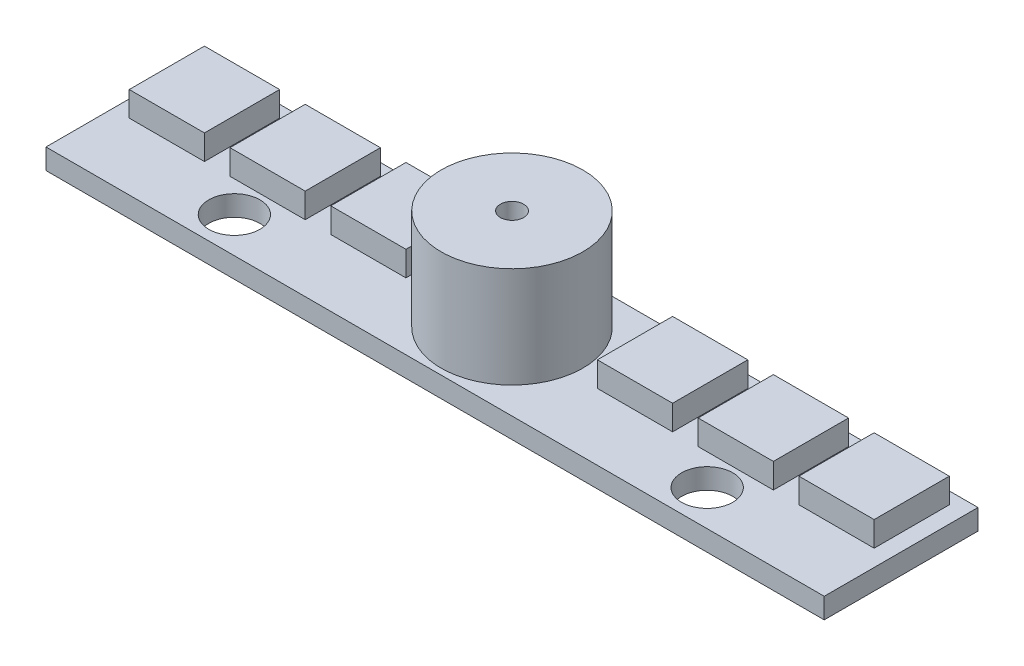
SolidWorks part; units mm, degrees
ref_plane "Front Plane" through (0, 0, 0) normal (0, 0, 1) x (1, 0, 0)
ref_plane "Top Plane" through (0, 0, 0) normal (0, 1, 0) x (1, 0, 0)
ref_plane "Right Plane" through (0, 0, 0) normal (1, 0, 0) x (0, 0, -1)
sketch "Sketch1" plane through (0, 0, 0) normal (0, 1, 0) x (1, 0, 0)
  line L0 (0, 4.96) -> (0, -4.96) construction
  line L1 (-25.1, 4.96) -> (25.1, 4.96)
  line L2 (-25.1, 4.96) -> (-25.1, -4.96)
  line L3 (-25.1, -4.96) -> (25.1, -4.96)
  line L4 (25.1, 4.96) -> (25.1, -4.96)
  line L5 (-25.1, 4.96) -> (25.1, -4.96) construction
  line L6 (-25.1, -4.96) -> (25.1, 4.96) construction
  line L7 (-25.1, -2.66) -> (25.1, -2.66) construction
  circle A0 centre (-15.25, -2.66) radius 1.65
  circle A1 centre (15.25, -2.66) radius 1.65
  point P0 (0, 0)
  dimension "D4" = 3.3
  dimension "D1" = 9.92
  dimension "D2" = 50.2
  dimension "D3" = 2.3
  dimension "D5" = 30.5
extrude "Boss-Extrude1" add sketch "Sketch1" along normal blind 1.32
sketch "Sketch2" plane through (0, 1.32, 0) normal (0, 1, 0) x (1, 0, 0)
  line L0 (0, 4.96) -> (0, -4.96) construction
  line L1 (25.1, 4.96) -> (-25.1, 4.96) construction
  line L2 (-25.1, -4.96) -> (25.1, -4.96) construction
  circle A0 centre (0, 0) radius 4.575
  dimension "D1" = 9.15
extrude "Boss-Extrude2" add sketch "Sketch2" along normal blind 6.5
sketch "Sketch3" plane through (0, 7.82, 0) normal (0, 1, 0) x (1, 0, 0)
  circle A0 centre (0, 0) radius 0.75
  dimension "D1" = 1.5
extrude "Cut-Extrude1" cut sketch "Sketch3" against normal blind 1.5
sketch "Sketch4" plane through (0, 1.32, 0) normal (0, 1, 0) x (1, 0, 0)
  line L0 (-25.1, 1.76) -> (25.1, 1.76) construction
  line L1 (-25.1, 4.96) -> (-25.1, -4.96) construction
  line L2 (25.1, -4.96) -> (25.1, 4.96) construction
  line L3 (25.1, 4.96) -> (-25.1, 4.96) construction
  line L4 (0, 4.96) -> (0, -4.96) construction
  line L5 (-6.175, 4.185) -> (-11.025, 4.185)
  line L6 (-6.175, 4.185) -> (-6.175, -0.665)
  line L7 (-6.175, -0.665) -> (-11.025, -0.665)
  line L8 (-11.025, 4.185) -> (-11.025, -0.665)
  line L9 (-6.175, 4.185) -> (-11.025, -0.665) construction
  line L10 (-6.175, -0.665) -> (-11.025, 4.185) construction
  line L11 (-25.1, -4.96) -> (25.1, -4.96) construction
  line L12 (-12.675, 4.185) -> (-17.525, 4.185)
  line L13 (-17.525, 4.185) -> (-17.525, -0.665)
  line L14 (-12.675, -0.665) -> (-17.525, -0.665)
  line L15 (-12.675, 4.185) -> (-12.675, -0.665)
  line L16 (-19.175, 4.185) -> (-24.025, 4.185)
  line L17 (-24.025, 4.185) -> (-24.025, -0.665)
  line L18 (-19.175, -0.665) -> (-24.025, -0.665)
  line L19 (-19.175, 4.185) -> (-19.175, -0.665)
  line L20 (6.175, 4.185) -> (6.175, -0.665)
  line L21 (6.175, -0.665) -> (11.025, -0.665)
  line L22 (11.025, 4.185) -> (11.025, -0.665)
  line L23 (6.175, 4.185) -> (11.025, 4.185)
  line L24 (12.675, 4.185) -> (12.675, -0.665)
  line L25 (12.675, -0.665) -> (17.525, -0.665)
  line L26 (17.525, 4.185) -> (17.525, -0.665)
  line L27 (12.675, 4.185) -> (17.525, 4.185)
  line L28 (19.175, 4.185) -> (19.175, -0.665)
  line L29 (19.175, -0.665) -> (24.025, -0.665)
  line L30 (24.025, 4.185) -> (24.025, -0.665)
  line L31 (19.175, 4.185) -> (24.025, 4.185)
  point P8 (-8.6, 1.76)
  point P13 (-17.525, 1.76)
  dimension "D1" = 3.2
  dimension "D2" = 4.85
  dimension "D3" = 17.2
  dimension "D5" = 6.5
  dimension "D4" = 3
extrude "Boss-Extrude3" add sketch "Sketch4" along normal blind 1.6
